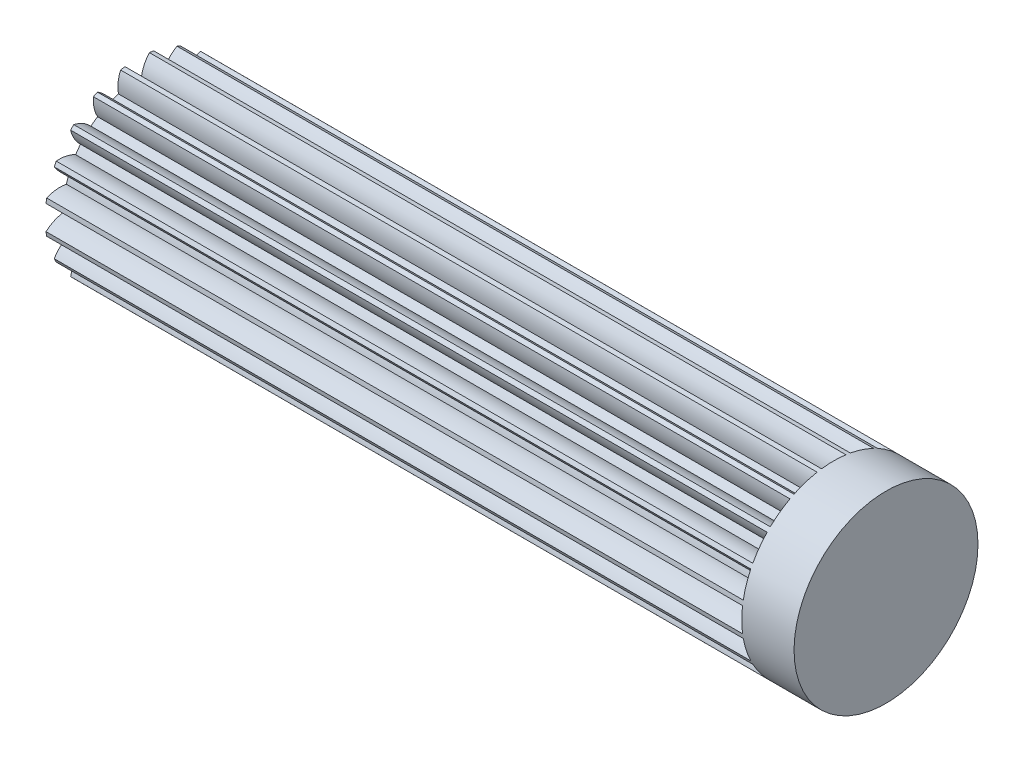
SolidWorks part; units mm, degrees
ref_plane "Plane1" through (0, 0, 0) normal (0, 0, 1) x (1, 0, 0)
ref_plane "Plane2" through (0, 0, 0) normal (0, 1, 0) x (1, 0, 0)
ref_plane "Plane3" through (0, 0, 0) normal (1, 0, 0) x (0, 0, -1)
sketch "HoldingSke" plane through (0, 0, 0) normal (0, 1, 0) x (1, 0, 0)
  line L0 (0, 0) -> (0.4698, -0.171)
  line L1 (-15, 0) -> (100, 0) construction
  line L2 (0, 0) -> (-2.1039, 2.3779)
  line L3 (0, 0) -> (-11.863, 4.5341)
  line L4 (0, 0) -> (8.1152, 2.9537)
  line L5 (0, 0) -> (-46.8476, -17.4728)
  line L6 (0, 0) -> (-9.9476, -6.7116)
  line L7 (-2.1039, 2.3779) -> (8.6586, 51.2059)
  line L8 (-76.2, 54.61) -> (-76.1, 54.61)
  line L9 (-71.009, 38.7566) -> (-53.1078, 45.2721)
  line L10 (-76.2, 71.12) -> (104.1128, 71.12)
  line L11 (0, 0) -> (-12, 0)
  line L12 (-76.2, 101.6) -> (-76.133, 101.6)
  line L13 (24.9733, 27.94) -> (52.9518, 28.4284)
  line L14 (24.9733, 27.94) -> (24.9743, 27.94)
  line L15 (24.9733, 27.94) -> (100.4006, 29.5858)
  line L16 (-63.627, -2) -> (-12.827, -2)
  circle A0 centre (0, 0) radius 0.4
  circle A1 centre (0, 0) radius 17.499
  circle A2 centre (0, 0) radius 37.5
  circle A3 centre (0, 0) radius 0.4
  dimension "MHD" = 34.998
  dimension "Hub_dia" = 75
  dimension "Bore" = 0.8
  dimension "MBD" = 0.8
  dimension "Num_teeth" = 20
  dimension "Pitch" = 0.5
  dimension "Overall_len" = 50
  dimension "Show_teeth" = 20
  dimension "Thickness" = 12
  dimension "OAL" = 50.0001
  dimension "T_dim" = 0.1
  dimension "Ap" = 20
  dimension "H" = 19.05
  dimension "Pitch_radius" = 180.3128
  dimension "Width" = 12
  dimension "Backlash" = 0.067
  dimension "Addendum_fac" = 1
  dimension "Dedendum_fac" = 1.25
  dimension "Clearance_fac" = 0.25
  dimension "Dedendum_add" = 0.001
  dimension "Module" = 2
sketch "BasProSke" plane through (0, 0, 0) normal (0, 1, 0) x (1, 0, 0)
  line L0 (-10, 0) -> (60, 0) construction
  line L1 (0, 0) -> (0, 22)
  line L2 (0, 0) -> (166.5933, 0)
  line L3 (166.5933, 0) -> (166.5933, 22)
  line L4 (166.5933, 22) -> (0, 22)
  dimension "Thickness" = 166.5933
  dimension "Diameter" = 44
revolve "Base-Revolve" add sketch "BasProSke" angle 360 about L0
sketch "TooCutSke" plane through (0, 0, 0) normal (1, 0, 0) x (0, 0, -1)
  line L1 (0, 0) -> (0, 107) construction
  line L2 (0, 0) -> (-1.6864, 19.9288) construction
  line L3 (0, 0) -> (-6.2409, 39.4033) construction
  line L4 (-1.6864, 19.9288) -> (-3.1204, 19.7016) construction
  arc A0 (0.9862, 17.4712) -> (-0.9862, 17.4712) centre (0, 0) ccw
  arc A1 (2.9329, 21.8293) -> (-2.9329, 21.8293) centre (0, 0) ccw
  circle A2 centre (0, 0) radius 20 construction
  circle A3 centre (0, 0) radius 18.7939 construction
  arc A4 (-0.9862, 17.4712) -> (-2.9329, 21.8293) centre (-8.9313, 16.536) ccw
  arc A5 (2.9329, 21.8293) -> (0.9862, 17.4712) centre (8.9313, 16.536) ccw
  dimension "Root_dia" = 34.998
  dimension "Overcut_dia" = 44.0508
  dimension "Pitch_dia" = 40
  dimension "Base_dia" = 37.5877
  dimension "Flank_rad" = 8
  dimension "Half_ang" = 9
  dimension "Half_CT" = 1.4519
extrude "ToothCut" cut sketch "TooCutSke" along normal through all
fillet "Breaks" [suppressed] radius 0.04
fillet "RootFillets" [suppressed] radius 0.501
pattern_circular "TeethCuts" count 20 every 18 about axis through (-10, 0, 0) along (1, 0, 0) of "ToothCut", "RootFillets", "Breaks"
sketch "HubNeaOneSke" plane through (0, 0, 0) normal (-1, 0, 0) x (0, 0, 1)
  circle A0 centre (0, 0) radius 17.499
  dimension "Diameter" = 34.998
extrude "HubNearOne" [suppressed] add sketch "HubNeaOneSke" along normal blind 38.0001
sketch "HubNeaBotSke" plane through (0, 0, 0) normal (-1, 0, 0) x (0, 0, 1)
  circle A0 centre (0, 0) radius 17.499
  dimension "Diameter" = 34.998
extrude "HubNearBoth" [suppressed] add sketch "HubNeaBotSke" along normal blind 19
ref_plane "FarPln" through (166.5933, 0, 0) normal (1, 0, 0) x (0, 0, -1)
sketch "HubFarSke" plane through (166.5933, 0, 0) normal (1, 0, 0) x (0, 0, -1)
  circle A0 centre (0, 0) radius 17.499
  dimension "Diameter" = 34.998
extrude "HubFar" [suppressed] add sketch "HubFarSke" along normal blind 19
sketch "BorSke" plane through (0, 0, 0) normal (1, 0, 0) x (0, 0, -1)
  circle A0 centre (0, 0) radius 0.4
  dimension "Diameter" = 0.8
extrude "Bore" cut sketch "BorSke" along normal mid plane 100.0001
sketch "KeySke" plane through (0, 0, 0) normal (1, 0, 0) x (0, 0, -1)
  line L0 (-0.05, 0) -> (-0.05, 0.5)
  line L1 (-0.05, 0.5) -> (0.05, 0.5)
  line L2 (0.05, 0.5) -> (0.05, 0)
  line L3 (0, 0) -> (0, 34) construction
  line L4 (-0.05, 0) -> (0.05, 0)
  dimension "Offset" = 0.5
  dimension "Width" = 0.1
extrude "Keyway" [suppressed] cut sketch "KeySke" along normal mid plane 100.0001
pattern_circular "Keyway2" [suppressed] count 2 every 90 about axis through (-10, 0, 0) along (1, 0, 0)
scale "Scale1" scale about centroid uniform scaling yes scale factor 0.399752
sketch "Sketch3" plane through (50.003, 0, 0) normal (-1, 0, 0) x (0, 0, 1)
  circle A0 centre (0, 0) radius 2.5
  dimension "D1" = 5
extrude "Cut-Extrude3" cut sketch "Sketch3" against normal blind 2
sketch "Sketch4" plane through (52.003, 0, 0) normal (-1, 0, 0) x (0, 0, 1)
  line L0 (2.2347, 1.1208) -> (1.7017, -1.8315)
  arc A0 (2.2347, 1.1208) -> (1.7017, -1.8315) centre (0, 0) ccw
  dimension "D1" = 3
extrude "Cut-Extrude4" cut sketch "Sketch4" against normal blind 19.8
sketch "Sketch5" plane through (116.5989, 0, 0) normal (1, 0, 0) x (0, 0, -1)
  circle A0 centre (0, 0) radius 8.7945
extrude "Boss-Extrude1" add sketch "Sketch5" along normal blind 5
equation "' \"Module@HoldingSke\" = 6.35"
equation "' \"Num_teeth@HoldingSke\" = 12"
equation "' \"Ap@HoldingSke\" =  20"
equation "' \"Ap@HoldingSke\" = 20"
equation "' \"Width@HoldingSke\" = 0.5 * 25.4"
equation "' \"Hub_dia@HoldingSke\"= 1 * 25.4"
equation "' \"Hub_dia@HoldingSke\" = 1 * 25.4"
equation "' \"Overall_len@HoldingSke\" = 1.0 * 25.4"
equation "' \"Bore@HoldingSke\" = 0.75 * 25.4"
equation "' \"T_dim@HoldingSke\" = 0.1 * 25.4"
equation "' \"Width@KeySke\" = 0.25 * 25.4"
equation "' \"Show_teeth@HoldingSke\" = 13"
equation "' \"Backlash@HoldingSke\" = 0.009 * 25.4"
equation "' \"Addendum_fac@HoldingSke\" = 1.0"
equation "' \"Dedendum_fac@HoldingSke\" = 1.25"
equation "' \"Dedendum_add@HoldingSke\" = 0.00005 * 25.4"
equation "' \"Clearance_fac@HoldingSke\" = 0.25"
equation "\"Pitch@HoldingSke\" = 1 / \"Module@HoldingSke\""
equation "\"Overcut_dia@TooCutSke\" = (\"Num_teeth@HoldingSke\" + 2 * \"Addendum_fac@HoldingSke\") / \"Pitch@HoldingSke\" + 0.002 * 25.4"
equation "\"Pitch_dia@TooCutSke\" = \"Num_teeth@HoldingSke\" / \"Pitch@HoldingSke\""
equation "\"Base_dia@TooCutSke\" = \"Num_teeth@HoldingSke\" / \"Pitch@HoldingSke\" * cos((\"Ap@HoldingSke\"  * 3.14159265 / 180))"
equation "\"Root_dia@TooCutSke\" = (\"Num_teeth@HoldingSke\" + 2) / \"Pitch@HoldingSke\" - 2 * (\"Addendum_fac@HoldingSke\" + \"Dedendum_fac@HoldingSke\") / \"Pitch@HoldingSke\" - \"Dedendum_add@HoldingSke\" * 2"
equation "\"Half_ang@TooCutSke\" = 180 / \"Num_teeth@HoldingSke\""
equation "\"Half_CT@TooCutSke\" = \"Num_teeth@HoldingSke\" / \"Pitch@HoldingSke\" * sin((3.14159265 / 2 / \"Num_teeth@HoldingSke\")) / 2 - 7 * \"Backlash@HoldingSke\" / 4"
equation "\"Flank_rad@TooCutSke\" = \"Num_teeth@HoldingSke\" / \"Pitch@HoldingSke\" / 5"
equation "\"Radius@RootFillets\" = \"Clearance_fac@HoldingSke\" / \"Pitch@HoldingSke\" + \"Dedendum_add@HoldingSke\""
equation "\"Break_rad@Breaks\" = 0.02 / \"Pitch@HoldingSke\""
equation "\"Thickness@HoldingSke\" = \"Width@HoldingSke\""
equation "\"OAL@HoldingSke\" = \"Thickness@HoldingSke\""
equation "\"MHD@HoldingSke\" = (\"Num_teeth@HoldingSke\" + 2) / \"Pitch@HoldingSke\" - 2 * (\"Addendum_fac@HoldingSke\" + \"Dedendum_fac@HoldingSke\")  / \"Pitch@HoldingSke\" - \"Dedendum_add@HoldingSke\" * 2"
equation "\"MBD@HoldingSke\" = (\"Num_teeth@HoldingSke\" + 2) / \"Pitch@HoldingSke\" - 2 * (\"Addendum_fac@HoldingSke\" + \"Dedendum_fac@HoldingSke\")  / \"Pitch@HoldingSke\" - \"Dedendum_add@HoldingSke\" * 2 - 0.002 * 25.4"
equation "\"MHD@HoldingSke\" = ((sgn( \"MHD@HoldingSke\" - \"Hub_dia@HoldingSke\" )-1)*( \"MHD@HoldingSke\" - \"Hub_dia@HoldingSke\" ))/-2+ \"Hub_dia@HoldingSke\""
equation "\"MBD@HoldingSke\" = ((sgn( \"MBD@HoldingSke\" - \"Bore@HoldingSke\" )-1)*( \"MBD@HoldingSke\" - \"Bore@HoldingSke\" ))/-2+ \"Bore@HoldingSke\""
equation "\"OAL@HoldingSke\" = ((sgn( \"OAL@HoldingSke\" - \"Overall_len@HoldingSke\" )+1)*( \"OAL@HoldingSke\" - \"Overall_len@HoldingSke\" ))/2 + \"Overall_len@HoldingSke\" + 0.000002 * 25.4"
equation "\"Num_teeth@TeethCuts\" = int( \"Show_teeth@HoldingSke\" ) + 1"
equation "\"Num_teeth@TeethCuts\" = ((sgn( \"Num_teeth@TeethCuts\" - \"Num_teeth@HoldingSke\" )-1)*( \"Num_teeth@TeethCuts\" - \"Num_teeth@HoldingSke\" ))/-2+ \"Num_teeth@HoldingSke\""
equation "\"Num_teeth@TeethCuts\" = ((sgn( \"Num_teeth@TeethCuts\" - 2.0)+1)*( \"Num_teeth@TeethCuts\" - 2.0))/2 +2.0"
equation "\"Angle@TeethCuts\" = 360.0 / \"Num_teeth@HoldingSke\""
equation "\"Diameter@BasProSke\" = (\"Num_teeth@HoldingSke\" + 2 * \"Addendum_fac@HoldingSke\") / \"Pitch@HoldingSke\""
equation "\"Thickness@BasProSke\"=(36.6153564+30)*85.028/34"
equation "' \"Fillet_rad@BasProSke\" =  \"Thickness@HoldingSke\" * 0.05"
equation "' \"Fillet_rad@BasProSke\" = \"Thickness@HoldingSke\" * 0.05"
equation "\"MHD@HoldingSke\" = ((sgn( \"MHD@HoldingSke\" - \"Root_dia@TooCutSke\" )-1)*( \"MHD@HoldingSke\" - \"Root_dia@TooCutSke\" ))/-2+ \"Root_dia@TooCutSke\""
equation "\"Diameter@HubNeaOneSke\" = \"MHD@HoldingSke\""
equation "\"Length@HubNearOne\" = \"OAL@HoldingSke\" - \"Thickness@BasProSke\""
equation "\"Diameter@HubNeaBotSke\" = \"MHD@HoldingSke\""
equation "\"Length@HubNearBoth\" = ( \"OAL@HoldingSke\" - \"Thickness@BasProSke\" ) / 2.0"
equation "\"Thickness@FarPln\" = \"Thickness@BasProSke\""
equation "\"Diameter@HubFarSke\" = \"MHD@HoldingSke\""
equation "\"Length@HubFar\" = ( \"OAL@HoldingSke\" - \"Thickness@BasProSke\" ) / 2.0"
equation "\"Diameter@BorSke\" = \"MBD@HoldingSke\""
equation "\"D1@Bore\" = \"OAL@HoldingSke\" * 2.0"
equation "\"D1@Keyway\" = \"OAL@HoldingSke\" * 2.0"
equation "\"Offset@KeySke\" = \"T_dim@HoldingSke\" + \"MBD@HoldingSke\" / 2.0"
